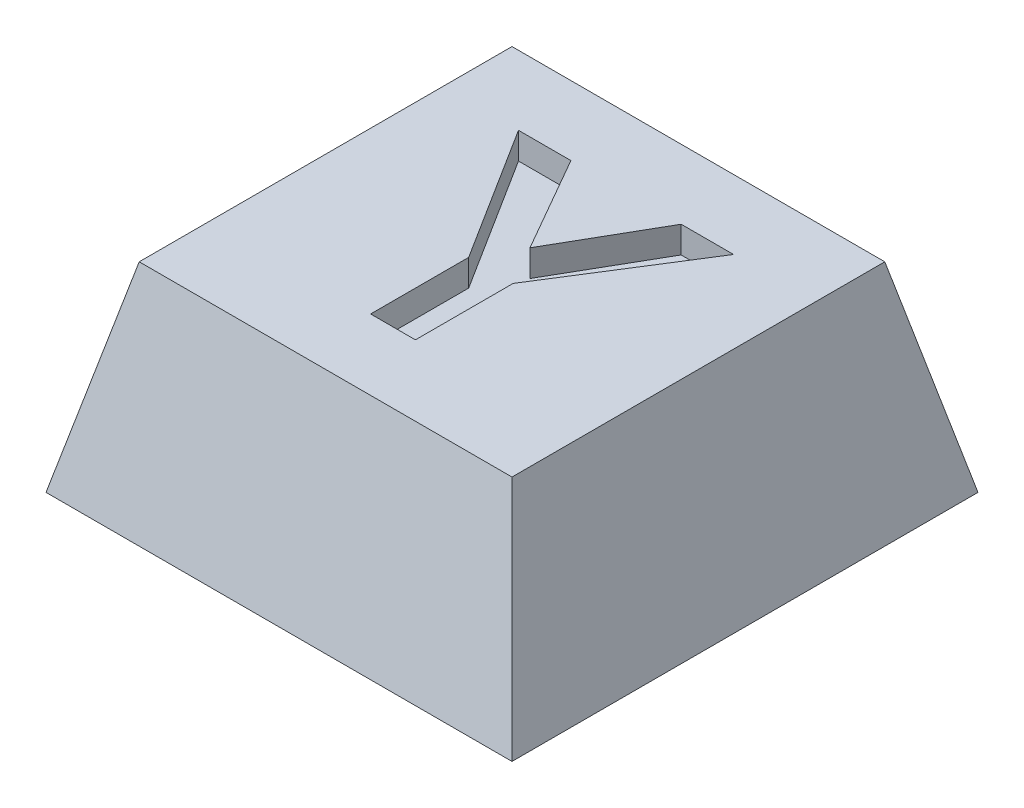
SolidWorks part; units mm, degrees
ref_plane "Front Plane" through (0, 0, 0) normal (0, 0, 1) x (1, 0, 0)
ref_plane "Top Plane" through (0, 0, 0) normal (0, 1, 0) x (1, 0, 0)
ref_plane "Right Plane" through (0, 0, 0) normal (1, 0, 0) x (0, 0, -1)
sketch "Sketch1" plane through (0, 0, 0) normal (0, 1, 0) x (1, 0, 0)
  line L1 (0, 0) -> (7, 0)
  line L2 (0, 0) -> (0, 7)
  line L3 (0, 7) -> (7, 7)
  line L4 (7, 0) -> (7, 7)
  dimension "D1" = 7
  dimension "D2" = 7
extrude "Boss-Extrude1" add sketch "Sketch1" along normal blind 3
sketch "Sketch2" plane through (0, 0, 0) normal (0, 0, 1) x (1, 0, 0)
  line L0 (0, 0) -> (0.7, 3)
  line L1 (0, 3) -> (7, 3) construction
  line L2 (0.7, 3) -> (0, 3)
  line L3 (0, 3) -> (0, 0)
  line L4 (7, 0) -> (6.3, 3)
  line L5 (6.3, 3) -> (7, 3)
  line L6 (7, 3) -> (7, 0)
  dimension "D1" = 0.7
  dimension "D2" = 0.7
extrude "Cut-Extrude1" cut sketch "Sketch2" against normal blind 7
sketch "Sketch3" plane through (0, 0, 0) normal (1, 0, 0) x (0, 0, -1)
  line L0 (0, 0) -> (0.7, 3)
  line L1 (7, 3) -> (0, 3) construction
  line L2 (0.7, 3) -> (0, 3)
  line L3 (0, 3) -> (0, 0)
  line L4 (7, 3) -> (6.3, 3)
  line L5 (6.3, 3) -> (7, 0)
  line L6 (7, 3) -> (7, 0)
  dimension "D1" = 0.7
  dimension "D2" = 0.7
extrude "Cut-Extrude2" cut sketch "Sketch3" along normal blind 11
sketch "Sketch4" plane through (0, 0, 0) normal (0, -1, 0) x (1, 0, 0)
  line L0 (3.5, 0) -> (3.5, -7) construction
  line L1 (0, 0) -> (7, 0) construction
  line L2 (7, -7) -> (0, -7) construction
  line L3 (0, -3.5) -> (7, -3.5) construction
  line L4 (0, -7) -> (0, 0) construction
  line L5 (7, 0) -> (7, -7) construction
  circle A0 centre (3.5, -3.5) radius 1.8
  dimension "D1" = 3.6
extrude "Cut-Extrude3" cut sketch "Sketch4" against normal blind 0.8
sketch "Sketch5" plane through (0, 3, 0) normal (0, 1, 0) x (1, 0, 0)
  text T0 "Y" font "Arial" height 3.5
extrude "Cut-Extrude4" cut sketch "Sketch5" against normal blind 0.4
